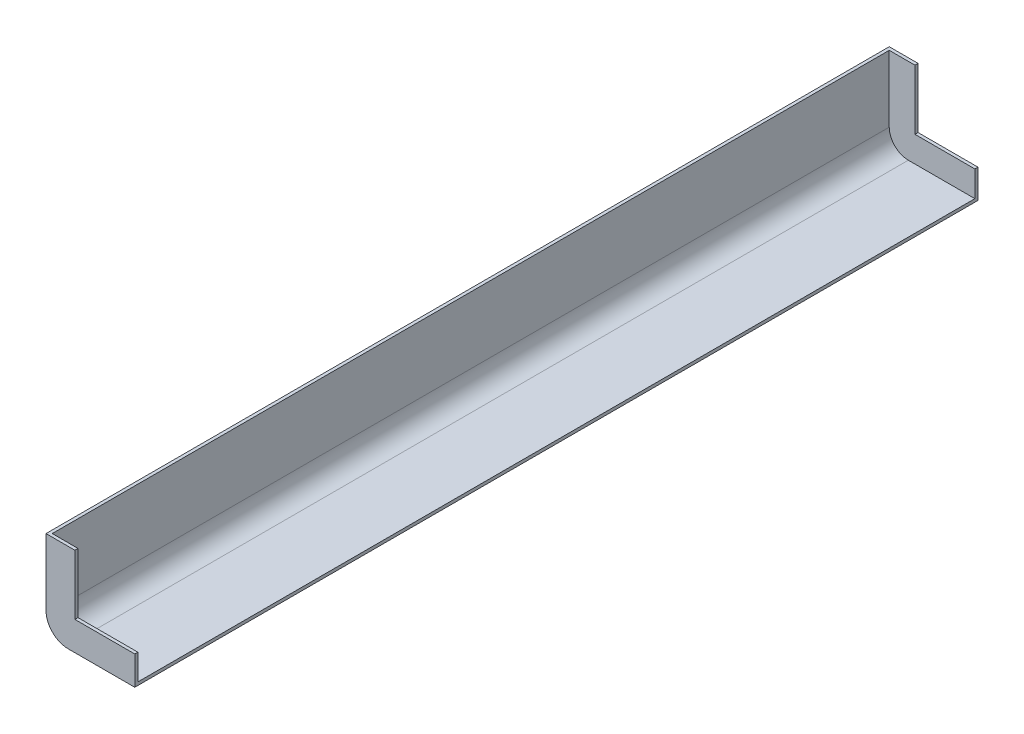
SolidWorks part; units mm, degrees
material "Alloy Steel"
ref_plane "Front Plane" through (0, 0, 0) normal (0, 0, 1) x (1, 0, 0)
ref_plane "Top Plane" through (0, 0, 0) normal (0, 1, 0) x (1, 0, 0)
ref_plane "Right Plane" through (0, 0, 0) normal (1, 0, 0) x (0, 0, -1)
sketch "Sketch1" plane through (0, 0, 0) normal (0, 0, 1) x (1, 0, 0)
  line L0 (0, 12.7) -> (0, 50.8)
  line L1 (12.7, 0) -> (50.8, 0)
  line L2 (50.8, 0) -> (50.8, 16.51)
  line L3 (50.8, 16.51) -> (16.51, 16.51)
  line L4 (16.51, 16.51) -> (16.51, 50.8)
  line L5 (16.51, 50.8) -> (0, 50.8)
  arc A0 (0, 12.7) -> (12.7, 0) centre (12.7, 12.7) ccw
  point P9 (0, 0)
  dimension "D5" = 12.7
  dimension "D1" = 50.8
  dimension "D2" = 50.8
  dimension "D3" = 16.51
  dimension "D4" = 16.51
extrude "Boss-Extrude1" add sketch "Sketch1" along normal blind 482.6
shell "Shell1" thickness 1.778
